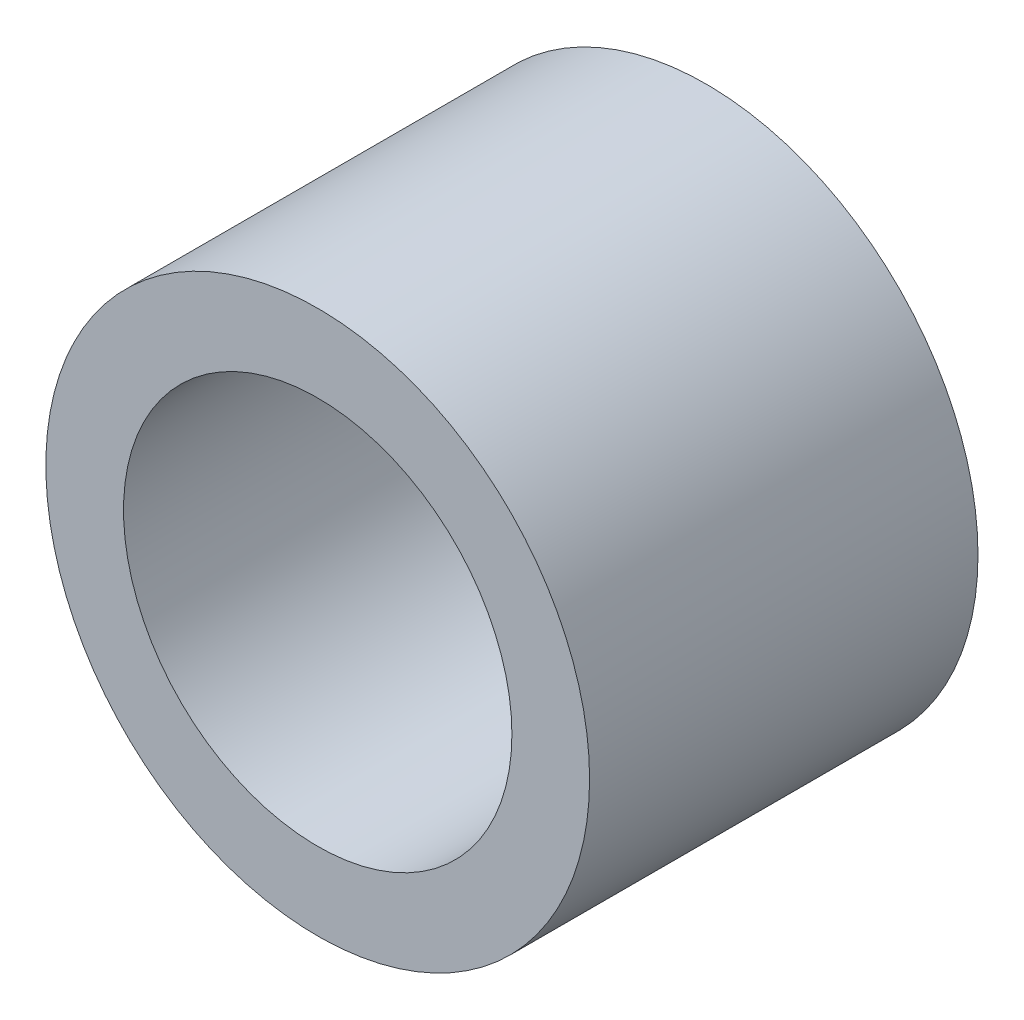
SolidWorks part; units mm, degrees
ref_plane "Front Plane" through (0, 0, 0) normal (0, 0, 1) x (1, 0, 0)
ref_plane "Top Plane" through (0, 0, 0) normal (0, 1, 0) x (1, 0, 0)
ref_plane "Right Plane" through (0, 0, 0) normal (1, 0, 0) x (0, 0, -1)
other "Configuration Table"
sketch "Sketch1" plane through (0, 0, 0) normal (0, 0, 1) x (1, 0, 0)
  circle A0 centre (0, 0) radius 2.5
  circle A1 centre (0, 0) radius 3.5
extrude "Boss-Extrude1" add sketch "Sketch1" along normal blind 5
